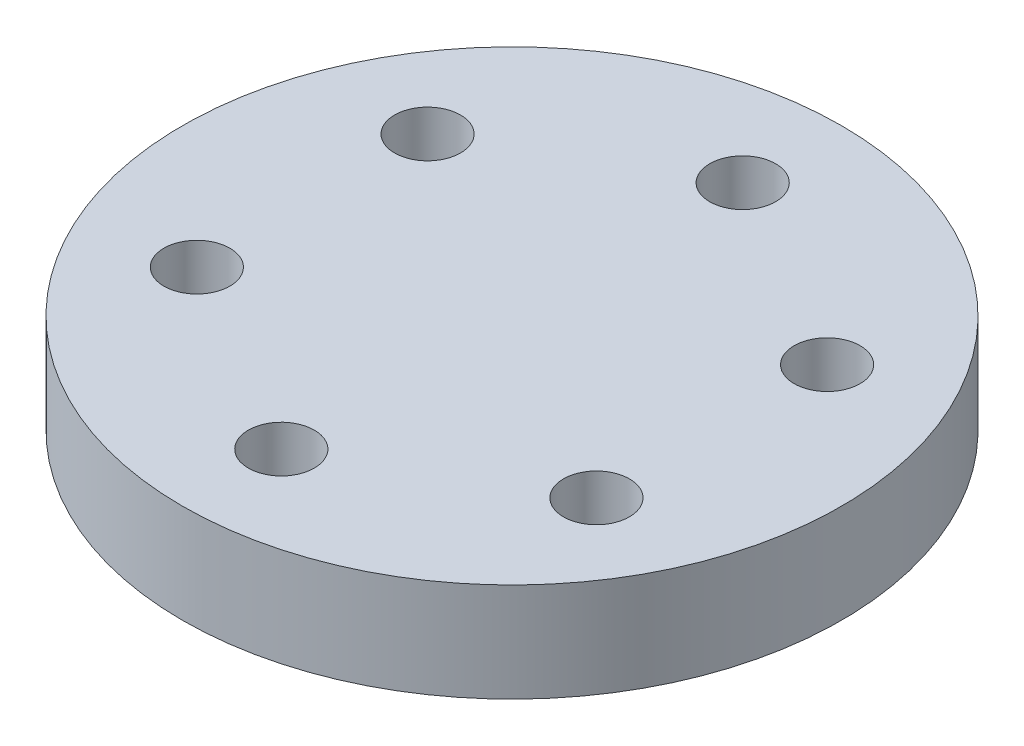
SolidWorks part; units mm, degrees
ref_plane "Front Plane" through (0, 0, 0) normal (0, 0, 1) x (1, 0, 0)
ref_plane "Top Plane" through (0, 0, 0) normal (0, 1, 0) x (1, 0, 0)
ref_plane "Right Plane" through (0, 0, 0) normal (1, 0, 0) x (0, 0, -1)
sketch "Sketch1" plane through (0, 0, 0) normal (0, 1, 0) x (1, 0, 0)
  circle A0 centre (0, 0) radius 50
  dimension "D1" = 100
extrude "Boss-Extrude1" add sketch "Sketch1" along normal blind 15
sketch "Sketch2" plane through (0, 15, 0) normal (0, 1, 0) x (1, 0, 0)
  circle A0 centre (0, 0) radius 35
  circle A1 centre (0, 35) radius 5
  dimension "D1" = 70
  dimension "D2" = 10
extrude "Cut-Extrude2" cut sketch "Sketch2" against normal through all contours A0 A1 | A0 A1
pattern_circular "CirPattern1" count 6 every 60 about axis through (0, 0, 0) along (0, 1, 0) of "Cut-Extrude2"
